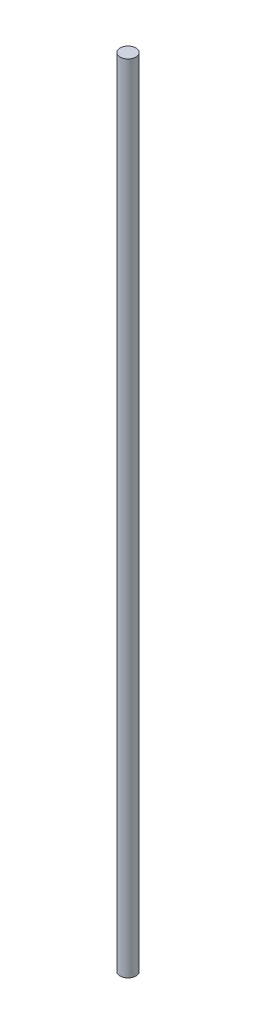
SolidWorks part; units mm, degrees
ref_plane "正面" through (0, 0, 0) normal (0, 0, 1) x (1, 0, 0)
ref_plane "平面" through (0, 0, 0) normal (0, 1, 0) x (1, 0, 0)
ref_plane "右側面" through (0, 0, 0) normal (1, 0, 0) x (0, 0, -1)
sketch "ｽｹｯﾁ1" plane through (0, 0, 0) normal (0, 1, 0) x (1, 0, 0)
  circle A0 centre (0, 0) radius 1
  dimension "D1" = 2
extrude "ﾎﾞｽ - 押し出し1" add sketch "ｽｹｯﾁ1" along normal blind 100
